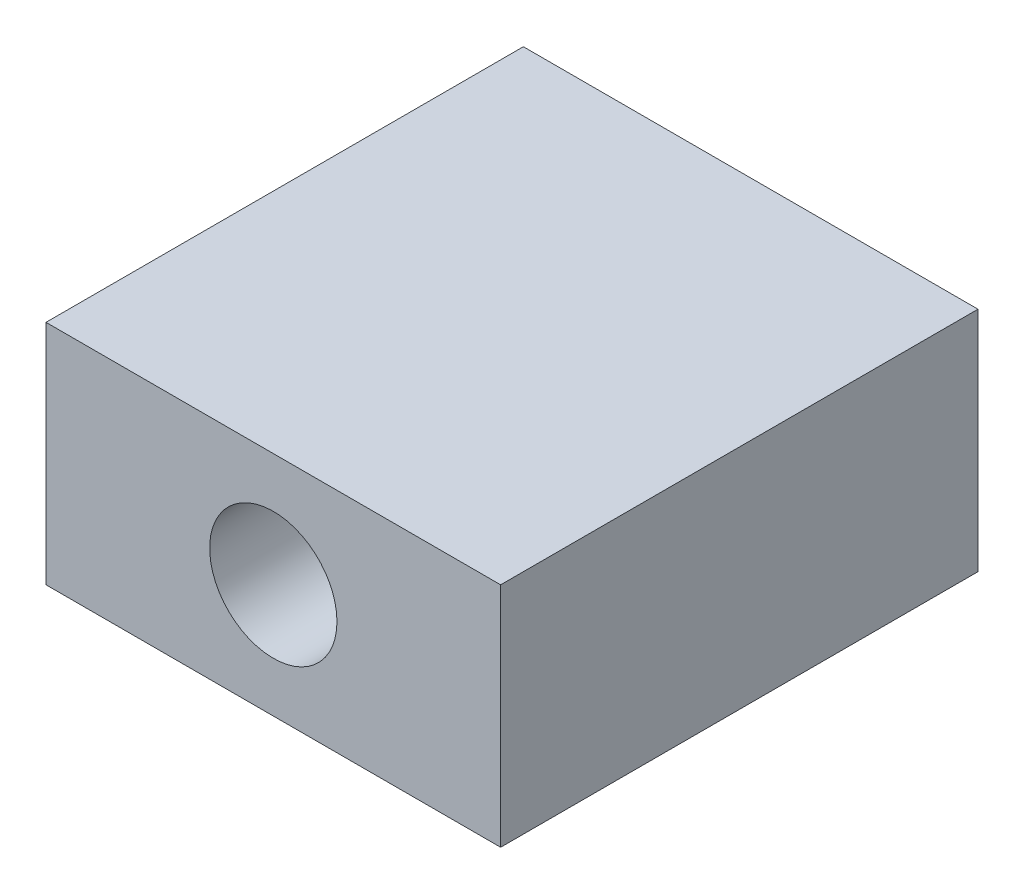
SolidWorks part; units mm, degrees
ref_plane "Front Plane" through (0, 0, 0) normal (0, 0, 1) x (1, 0, 0)
ref_plane "Top Plane" through (0, 0, 0) normal (0, 1, 0) x (1, 0, 0)
ref_plane "Right Plane" through (0, 0, 0) normal (1, 0, 0) x (0, 0, -1)
sketch "Sketch1" plane through (0, 0, 0) normal (0, 1, 0) x (1, 0, 0)
  line L1 (0, 0) -> (63.5, 0)
  line L2 (0, 0) -> (0, 66.675)
  line L3 (0, 66.675) -> (63.5, 66.675)
  line L4 (63.5, 0) -> (63.5, 66.675)
  dimension "D1" = 63.5
  dimension "D2" = 66.675
extrude "Boss-Extrude1" add sketch "Sketch1" along normal blind 31.75
sketch "Sketch2" plane through (0, 0, 0) normal (0, 0, 1) x (1, 0, 0)
  circle A0 centre (31.75, 15.875) radius 8.89
  dimension "D3" = 17.78
  dimension "D1" = 31.75
  dimension "D2" = 15.875
extrude "Cut-Extrude1" cut sketch "Sketch2" against normal blind 12.7
